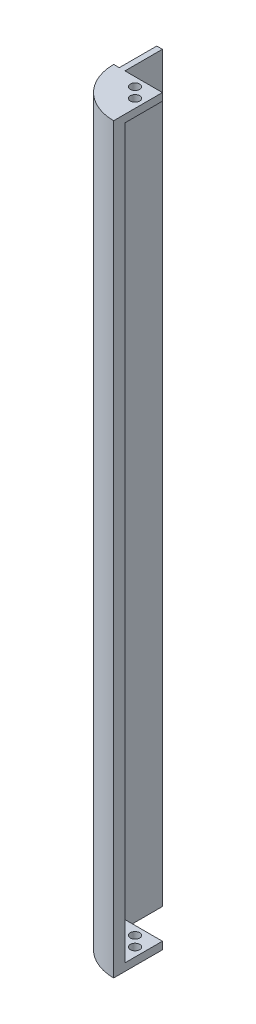
SolidWorks part; units mm, degrees
material "PET"
ref_plane "前视基准面" through (0, 0, 0) normal (0, 0, 1) x (1, 0, 0)
ref_plane "上视基准面" through (0, 0, 0) normal (0, 1, 0) x (1, 0, 0)
ref_plane "右视基准面" through (0, 0, 0) normal (1, 0, 0) x (0, 0, -1)
other "Configuration Table"
sketch "草图1" plane through (0, 0, 0) normal (0, 1, 0) x (1, 0, 0)
  line L1 (-15, 5.5) -> (15, 5.5)
  line L2 (-15, 5.5) -> (-15, -5.5)
  line L3 (-15, -5.5) -> (15, -5.5)
  line L4 (15, 5.5) -> (15, -5.5)
  line L5 (-15, 5.5) -> (15, -5.5) construction
  line L6 (-15, -5.5) -> (15, 5.5) construction
  point P0 (0, 0)
  dimension "D1" = 30
  dimension "D2" = 11
extrude "凸台-拉伸1" add sketch "草图1" along normal blind 6
sketch "草图2" plane through (-15, 0, 0) normal (-1, 0, 0) x (0, 0, 1)
  line L0 (-5.5, 6) -> (-5.5, 0) construction
  line L1 (-13.5, 2) -> (2.5, 2)
  line L2 (-13.5, 2) -> (-13.5, 4)
  line L3 (-13.5, 4) -> (2.5, 4)
  line L4 (2.5, 2) -> (2.5, 4)
  line L5 (-13.5, 2) -> (2.5, 4) construction
  line L6 (-13.5, 4) -> (2.5, 2) construction
  line L7 (-5.5, 6) -> (5.5, 6) construction
  line L8 (5.5, 6) -> (5.5, 0) construction
  point P0 (-5.5, 3)
  dimension "D1" = 2
  dimension "D2" = 3
extrude "切除-拉伸1" cut sketch "草图2" against normal blind 144
sketch "草图3" plane through (0, 6, 0) normal (0, 1, 0) x (1, 0, 0)
  line L0 (2, 5.5) -> (-2, 5.5)
  line L1 (15, 5.5) -> (-15, 5.5) construction
  line L2 (-2, 5.5) -> (-2, -3.5)
  line L3 (-2, -3.5) -> (-15, -3.5)
  line L4 (-15, 5.5) -> (-15, -5.5) construction
  line L5 (-15, -3.5) -> (-15, -5.5)
  line L6 (-15, -5.5) -> (15, -5.5)
  line L7 (-15, -5.5) -> (15, -5.5) construction
  line L8 (0, 5.5) -> (0, -5.5) construction
  line L9 (15, -3.5) -> (15, -5.5)
  line L10 (2, -3.5) -> (15, -3.5)
  line L11 (2, 5.5) -> (2, -3.5)
  dimension "D1" = 2
  dimension "D2" = 2
extrude "凸台-拉伸2" add sketch "草图3" along normal blind 192
sketch "草图4" plane through (0, 6, 0) normal (0, 1, 0) x (1, 0, 0)
  line L0 (-15, 5.5) -> (-15, 2) construction
  line L1 (-15, 5.5) -> (-15, -3.5) construction
  line L2 (-15, 2) -> (15, 2) construction
  line L3 (15, -3.5) -> (15, 5.5) construction
  line L4 (0, 5.5) -> (0, -5.5) construction
  line L5 (2, 5.5) -> (-2, 5.5) construction
  line L6 (-15, -5.5) -> (15, -5.5) construction
  circle A0 centre (-7.5, 2) radius 1.75
  circle A1 centre (7.5, 2) radius 1.75
  point P10 (0, 2)
  dimension "D2" = 7.5
  dimension "D3" = 3.5
  dimension "D1" = 3.5
extrude "切除-拉伸2" cut sketch "草图4" against normal blind 144
sketch "草图5" plane through (-15, 0, 0) normal (-1, 0, 0) x (0, 0, 1)
  line L1 (-5.5, 0) -> (5.5, 0)
  line L2 (-5.5, 0) -> (-5.5, 198)
  line L3 (-5.5, 198) -> (5.5, 198)
  line L4 (5.5, 0) -> (5.5, 198)
extrude "切除-拉伸3" cut sketch "草图5" against normal blind 2.5
sketch "草图6" plane through (0, 6, 0) normal (0, 1, 0) x (1, 0, 0)
  line L0 (-12.5, -2.5) -> (-12.5, 7.5) construction
  line L1 (-22.5, 7.5) -> (-25.5, 7.5)
  line L2 (-12.5, -2.5) -> (-12.5, -5.5)
  arc A0 (-22.5, 7.5) -> (-12.5, -2.5) centre (-12.5, 7.5) ccw
  arc A1 (-25.5, 7.5) -> (-12.5, -5.5) centre (-12.5, 7.5) ccw
  dimension "D1" = 10
extrude "凸台-拉伸3" add sketch "草图6" along normal up to surface and the other way up to surface up to face at (0.625, 198, 1.75) other way up to face at (7.5, 0, -0.25)
sketch "草图7" plane through (0, 0, -7.5) normal (0, 0, -1) x (-1, 0, 0)
  line L0 (25.5, 0) -> (22.5, 0) construction
  line L1 (22.5, 198) -> (24, 198)
  line L2 (22.5, 198) -> (22.5, 0)
  line L3 (22.5, 0) -> (24, 0)
  line L4 (24, 198) -> (24, 0)
  dimension "D1" = 1.5
extrude "凸台-拉伸4" add sketch "草图7" along normal blind 10
sketch "草图8" plane through (-12.5, 0, 0) normal (1, 0, 0) x (0, 0, -1)
  line L1 (-2.5, 198) -> (-26.7009, 198)
  line L2 (-2.5, 198) -> (-2.5, -9.5147)
  line L3 (-2.5, -9.5147) -> (-26.7009, -9.5147)
  line L4 (-26.7009, 198) -> (-26.7009, -9.5147)
  line L5 (-2.5, 198) -> (26.8925, 198)
  line L6 (-2.5, 198) -> (-2.5, -9.5147)
  line L7 (-2.5, -9.5147) -> (26.8925, -9.5147)
  line L8 (26.8925, 198) -> (26.8925, -9.5147)
  line M1 (-3.5, 198) -> (-3.5, 6)
  line M2 (-3.5, 6) -> (-2.5, 6)
  line M3 (-2.5, 6) -> (-2.5, 198)
extrude "切除-拉伸4" cut sketch "草图8" along normal blind 40 contours L8 L5 L2 L7 M3 | L1 L4 L3 L2 M2 M1
sketch "草图9" plane through (0, 198, 0) normal (0, 1, 0) x (1, 0, 0)
  line L0 (-12.5, -2.5) -> (-12.5, 7.5)
  line L1 (-12.5, 7.5) -> (-22.5, 7.5)
  arc A0 (-22.5, 7.5) -> (-12.5, -2.5) centre (-12.5, 7.5) ccw construction
  arc A1 (-22.5, 7.5) -> (-12.5, -2.5) centre (-12.5, 7.5) ccw
extrude "凸台-拉伸5" add sketch "草图9" against normal blind 2
sketch "草图10" plane through (0, 196, 0) normal (0, -1, 0) x (-1, 0, 0)
  line L0 (22.5, 7.5) -> (12.5, -2.5) construction
  line L1 (17.5, 2.5) -> (12.5, 2.5) construction
  line L2 (12.5, -2.5) -> (12.5, 7.5) construction
  line L3 (17.5, 2.5) -> (17.5, 7.5) construction
  line L4 (12.5, 7.5) -> (22.5, 7.5) construction
  circle A0 centre (14.8, 2.5) radius 1.25
  circle A1 centre (17.5, 5.2) radius 1.25
  dimension "D1" = 2.3
  dimension "D2" = 2.3
  dimension "D3" = 2.5
  dimension "D4" = 2.5
extrude "切除-拉伸5" cut sketch "草图10" against normal blind 3
ref_plane "基准面1" through (0, 99, 0) normal (0, -1, 0) x (-1, 0, 0)
mirror "镜向2" about plane through (0, 99, 0) normal (0, -1, 0) of "凸台-拉伸5", "切除-拉伸5"
